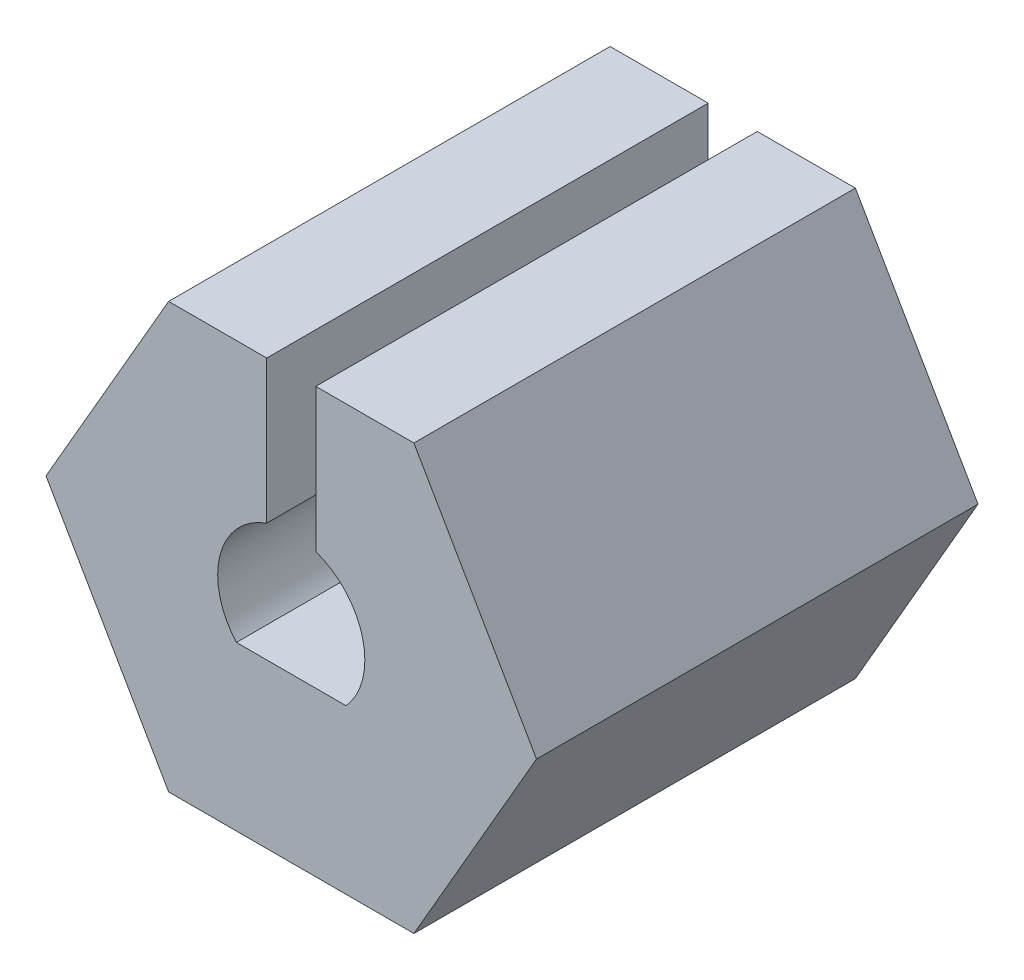
SolidWorks part; units mm, degrees
ref_plane "Front Plane" through (0, 0, 0) normal (0, 0, 1) x (1, 0, 0)
ref_plane "Top Plane" through (0, 0, 0) normal (0, 1, 0) x (1, 0, 0)
ref_plane "Right Plane" through (0, 0, 0) normal (1, 0, 0) x (0, 0, -1)
sketch "Sketch1" plane through (0, 0, 0) normal (0, 0, 1) x (1, 0, 0)
  line L0 (-1.118, -1) -> (1.118, -1)
  line L1 (5, 0) -> (2.5, 4.3301)
  line L2 (2.5, 4.3301) -> (-2.5, 4.3301)
  line L3 (-2.5, 4.3301) -> (-5, 0)
  line L4 (-5, 0) -> (-2.5, -4.3301)
  line L5 (-2.5, -4.3301) -> (2.5, -4.3301)
  line L6 (2.5, -4.3301) -> (5, 0)
  line L7 (0, 0) -> (0, 4.3301) construction
  line L8 (-0.5, 4.3301) -> (-0.5, 1.4142)
  line L9 (0.5, 4.3301) -> (0.5, 1.4142)
  circle A0 centre (0, 0) radius 5 construction
  circle A1 centre (0, 0) radius 1.5
  dimension "D1" = 10
  dimension "D2" = 3
  dimension "D3" = 1
  dimension "D4" = 0.5
  dimension "D5" = 0.5
extrude "Boss-Extrude1" add sketch "Sketch1" along normal blind 9 contours A1 L8 L2 L3 L4 L5 L6 L1 L9 | L0 A1
